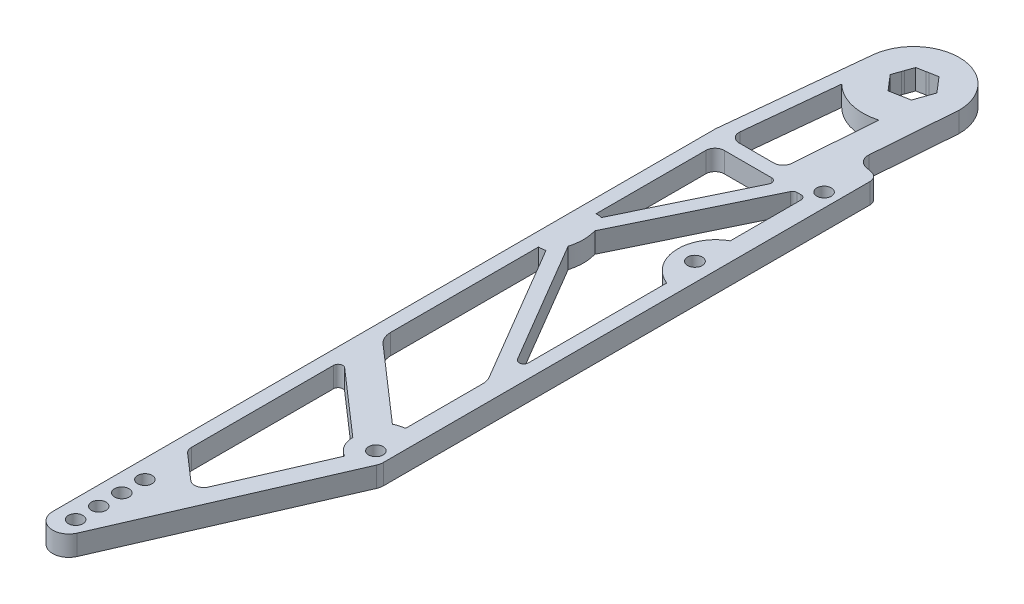
SolidWorks part; units mm, degrees
material "6061-T6 (SS)"
ref_plane "X-Y Datum" through (0, 0, 0) normal (0, 0, 1) x (1, 0, 0)
ref_plane "X-Z Datum" through (0, 0, 0) normal (0, 1, 0) x (1, 0, 0)
ref_plane "Y-Z Datum" through (0, 0, 0) normal (1, 0, 0) x (0, 0, -1)
other "Graphic1" [suppressed]
other "Graphic (Closed) -1" [suppressed]
sketch "Sketch2" plane through (0, 0, 0) normal (0, 1, 0) x (1, 0, 0)
  line L5 (13.4859, -161.3958) -> (-11.43, -139.6278) construction
  line L8 (0, 0) -> (0.7349, -24.1188) construction
  line L11 (15.3044, -26.8434) -> (13.2844, -26.3967)
  line L15 (-16.51, -220.3139) -> (-16.51, -38.0351)
  line L22 (-7.9887, -222.0863) -> (16.9799, -164.6625)
  line L23 (17.2959, -163.1433) -> (17.2959, -29.3235)
  line L33 (10.4385, -166.9668) -> (-0.894, -193.0299)
  line L44 (-8.8047, -78.8772) -> (8.7509, -42.6265)
  line L45 (9.8939, -41.91) -> (10.9459, -41.91)
  line L47 (11.153, -120.1131) -> (-8.8047, -86.2228)
  line L49 (-12.4132, -35.3011) -> (-9.8148, -9.9414)
  line L51 (3.8964, -13.4156) -> (2.1949, -35.7529)
  line L53 (-0.3377, -38.1) -> (-9.8864, -38.1)
  line L56 (2.8385, -41.91) -> (-10.16, -41.91)
  line L57 (13.97, -23.2966) -> (0, 0) construction
  line L58 (10.8042, -23.0554) -> (12.5603, 0)
  line L59 (-12.7, -146.862) -> (-12.7, -185.9568)
  line L63 (7.1359, -161.3958) -> (-10.5944, -145.9056)
  line L64 (-12.7, -74.6125) -> (-12.7, -44.45)
  line L65 (3.9815, -43.7335) -> (-11.056, -74.7846)
  line L66 (-16.4968, -37.7762) -> (-12.4949, 1.2803)
  line L67 (-4.8945, -193.9299) -> (-11.8311, -187.8696)
  line L68 (6.9813, -41.91) -> (-12.7, -82.55) construction
  line L69 (-1.1448, -63.0603) -> (-4.5739, -61.3997) construction
  line L70 (9.4184, -152.783) -> (-10.9623, -134.9772)
  line L71 (12.2159, -151.9558) -> (12.2159, -130.811)
  line L72 (11.5133, -128.2332) -> (-10.8443, -90.2675)
  line L75 (-12.7, -131.1516) -> (-12.7, -90.4875)
  line L76 (4.6927, 0.8838) -> (3.1117, -3.6221)
  line L77 (3.9022, -1.3692) -> (0, 0) construction
  line L78 (12.2159, -43.18) -> (12.2159, -62.6181)
  line L79 (13.5167, -81.4131) -> (13.5167, -119.4314)
  line L80 (0, 0) -> (-4.7752, 0) construction
  circle A0 centre (0, 0) radius 4.7752
  circle A2 centre (-11.43, -219.075) radius 2
  circle A3 centre (-11.43, -212.725) radius 2
  circle A4 centre (-11.43, -206.375) radius 2
  circle A5 centre (-11.43, -200.025) radius 2
  circle A7 centre (0, 0) radius 12.5603 construction
  circle A12 centre (13.4859, -38.1) radius 2
  arc A13 (-12.4949, 1.2803) -> (12.5603, 0) centre (0, 0) cw
  arc A14 (-8.8047, -86.2228) -> (-8.8047, -78.8772) centre (-20.962, -82.55) ccw
  circle A16 centre (24.0125, -12.7) radius 3.175 construction
  arc A17 (24.0125, -12.7) -> (13.97, -23.2966) centre (0, 0) cw construction
  circle A18 centre (13.97, -23.2966) radius 3.175 construction
  arc A19 (13.2844, -26.3967) -> (10.8042, -23.0554) centre (13.97, -23.2966) cw
  arc A20 (15.3044, -26.8434) -> (17.2959, -29.3235) centre (14.7559, -29.3235) cw
  circle A21 centre (13.4859, -161.3958) radius 2
  arc A24 (10.4385, -166.9668) -> (7.1359, -161.3958) centre (13.4859, -161.3958) cw
  arc A25 (-16.51, -220.3139) -> (-7.9887, -222.0863) centre (-12.065, -220.3139) ccw
  arc A26 (-12.7, -74.6125) -> (-11.056, -74.7846) centre (-12.7, -82.55) cw
  arc A28 (3.8964, -13.4156) -> (-9.8148, -9.9414) centre (0, 0) cw
  arc A31 (-10.16, -41.91) -> (-12.7, -44.45) centre (-10.16, -44.45) ccw
  arc A32 (-12.4132, -35.3011) -> (-9.8864, -38.1) centre (-9.8864, -35.56) ccw
  arc A33 (-0.3377, -38.1) -> (2.1949, -35.7529) centre (-0.3377, -35.56) ccw
  arc A36 (-12.7, -146.862) -> (-10.5944, -145.9056) centre (-11.43, -146.862) cw
  arc A37 (11.153, -120.1131) -> (13.5167, -119.4314) centre (12.2473, -119.4686) ccw
  arc A38 (8.7509, -42.6265) -> (9.8939, -41.91) centre (9.8939, -43.18) cw
  arc A39 (10.9459, -41.91) -> (12.2159, -43.18) centre (10.9459, -43.18) cw
  arc A40 (2.8385, -41.91) -> (3.9815, -43.7335) centre (2.8385, -43.18) cw
  arc A50 (17.2959, -163.1433) -> (16.9799, -164.6625) centre (13.4859, -163.1433) cw
  arc A52 (-16.4968, -37.7762) -> (-16.51, -38.0351) centre (-13.97, -38.0351) ccw
  arc A53 (-12.7, -185.9568) -> (-11.8311, -187.8696) centre (-10.16, -185.9568) ccw
  arc A54 (-4.8945, -193.9299) -> (-0.894, -193.0299) centre (-3.2233, -192.0171) ccw
  arc A55 (12.2159, -151.9558) -> (9.4184, -152.783) centre (13.4859, -161.3958) ccw
  arc A56 (-10.8443, -90.2675) -> (-12.7, -90.4875) centre (-12.7, -82.55) cw
  arc A57 (-12.7, -131.1516) -> (-10.9623, -134.9772) centre (-7.62, -131.1516) ccw
  arc A58 (11.5133, -128.2332) -> (12.2159, -130.811) centre (7.1359, -130.811) cw
  arc A59 (12.2159, -62.6181) -> (13.5167, -81.4131) centre (17.2959, -71.7091) ccw
  circle A60 centre (12.2159, -71.7091) radius 2.032
  point P30 (17.2959, -27.2838)
  point P44 (-2.8594, -62.23)
  point P45 (-2.2789, -196.215)
  point P75 (-4.7752, 0)
  point P88 (-12.7, -41.91)
  point P91 (-12.7, -38.1)
  point P104 (12.2159, -121.6534)
  point P107 (9.0979, -41.91)
  point P110 (13.3913, -41.91)
  point P120 (17.2959, -163.9358)
  dimension "D1" = 9.5504
  dimension "D6" = 4
  dimension "D5" = 25.1206
  dimension "D19" = 4
  dimension "D50" = 12.7
  dimension "D62" = 6.35
  dimension "D20" = 6.35
  dimension "D27" = 2.54
  dimension "D44" = 4
  dimension "D36" = 6.35
  dimension "D33" = 13.97
  dimension "D18" = 4.445
  dimension "D48" = 2.54
  dimension "D49" = 1.27
  dimension "D58" = 2.54
  dimension "D29" = 7.9375
  dimension "D31" = 3.81
  dimension "D41" = 2.54
  dimension "D54" = 9.525
  dimension "D55" = 7.9375
  dimension "D57" = 5.08
  dimension "D65" = 10.414
  dimension "D25" = 4.064
  dimension "D7" = 6.35
  dimension "D8" = 6.35
  dimension "D9" = 6.35
  dimension "D12" = 24.13
  dimension "D22" = 38.1
  dimension "D26" = 3.81
  dimension "D47" = 4.2935
  dimension "D51" = 8.262
  dimension "D56" = 3.81
  dimension "D21" = 136.652
  dimension "D43" = 200.025
  dimension "D10" = 5.08
  dimension "D28" = 38.1
  dimension "D60" = 24.0125
  dimension "D61" = 12.7
  dimension "D63" = 29.204
  dimension "D13" = 4.1084
  dimension "D17" = 13.97
  dimension "D24" = 3.81
  dimension "D30" = 2.54
  dimension "D46" = 7.62
  dimension "D11" = 5.08
  dimension "D23" = 13.4859
  dimension "D15" = 82.55
  dimension "D16" = 12.7
  dimension "D34" = 3.81
  dimension "D37" = 16.51
  dimension "D40" = 23.5
  dimension "D45" = 6.35
  dimension "D32" = 3.81
  dimension "D59" = 3.81
  dimension "D35" = 3.81
  dimension "D38" = 3.81
  dimension "D39" = 8.89
  dimension "D42" = 3.81
  dimension "D52" = 3.81
  dimension "D53" = 3.81
  dimension "D14" = 5.08
  dimension "D66" = 10.8409
  dimension "D67" = 5.08
  dimension "D64" = 4.7752
  dimension "D68" = 68.92
  dimension "D69" = 5.08
extrude "Boss-Extrude1" add sketch "Sketch2" along normal blind 5.588 contours L76 A0
sketch "Sketch6" plane through (-16.51, 0, 0) normal (-1, 0, 0) x (0, 0, 1)
  line L0 (182.2139, 5.588) -> (182.2139, 0)
  line L1 (220.3139, 0) -> (38.0351, 0) construction
  line L2 (220.3139, 5.588) -> (38.0351, 5.588) construction
  line L3 (220.3139, 5.588) -> (220.3139, 0) construction
  dimension "D1" = 38.1
split line "Split Line2"
sketch "Sketch7" plane through (0, 5.588, 0) normal (0, 1, 0) x (1, 0, 0)
  line L0 (17.2959, -163.1433) -> (17.2959, -29.3235) construction
  circle A0 centre (12.2159, -72.3621) radius 2.032
  dimension "D3" = 4.064
  dimension "D1" = 5.08
  dimension "D2" = 9.144
extrude "Cut-Extrude1" cut sketch "Sketch7" against normal up to surface (5.588 mm away) up to face at (-0.2638, 0, 126.3444)
sketch "Sketch8" plane through (0, 5.588, 0) normal (0, 1, 0) x (1, 0, 0)
  line L0 (4.6927, 0.8838) -> (3.1117, -3.6221) construction
  line L1 (1.8207, 5.1891) -> (-3.5835, 4.1713)
  line L2 (-3.5835, 4.1713) -> (-5.4043, -1.0178)
  line L3 (-5.4043, -1.0178) -> (-1.8207, -5.1891)
  line L4 (-1.8207, -5.1891) -> (3.5835, -4.1713)
  line L5 (3.5835, -4.1713) -> (5.4043, 1.0178)
  line L6 (5.4043, 1.0178) -> (1.8207, 5.1891)
  circle A0 centre (0, 0) radius 4.7625 construction
  point P2 (0, 0)
  point P3 (0, 0)
  point P4 (0, 0)
  point P5 (0, 0)
  point P6 (0, 0)
  point P7 (0, 0)
  dimension "D1" = 9.525
extrude "Cut-Extrude2" cut sketch "Sketch8" against normal through all
equation "\"D68@Sketch2\"=55.00+13.92"
